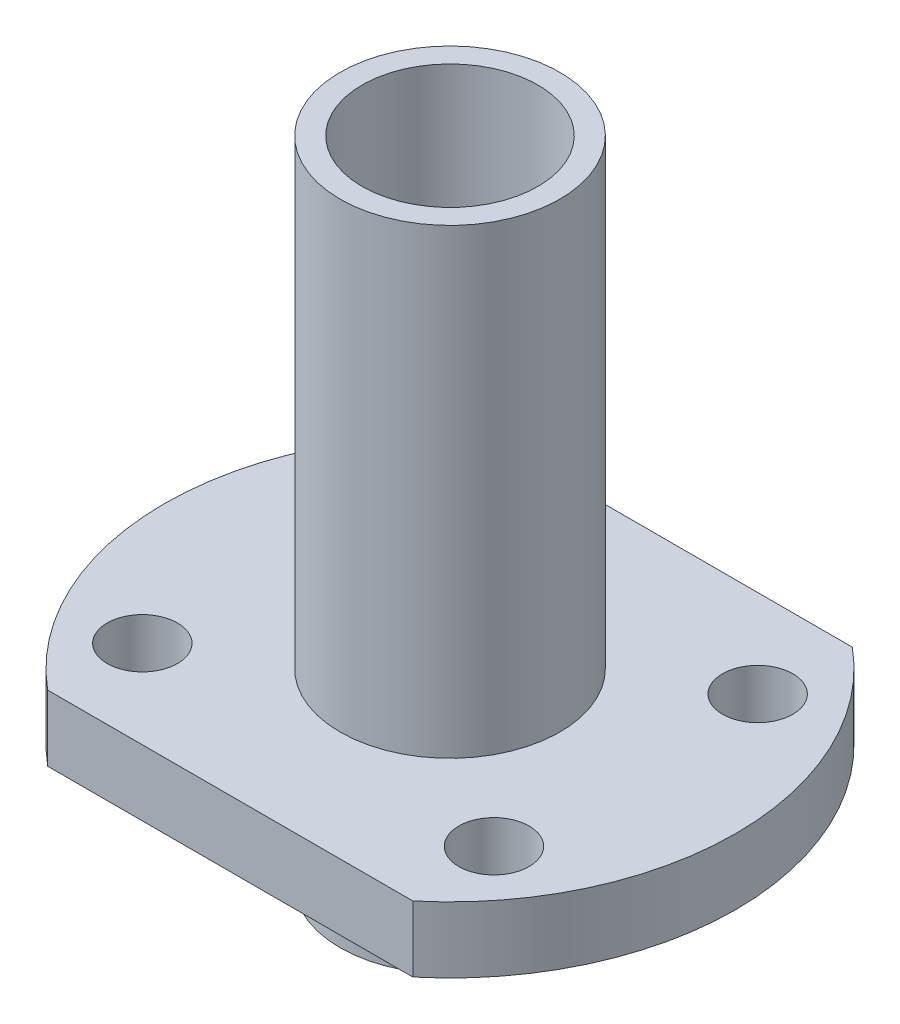
SolidWorks part; units mm, degrees
material "AISI 304"
ref_plane "Front Plane" through (0, 0, 0) normal (0, 0, 1) x (1, 0, 0)
ref_plane "Top Plane" through (0, 0, 0) normal (0, 1, 0) x (1, 0, 0)
ref_plane "Right Plane" through (0, 0, 0) normal (1, 0, 0) x (0, 0, -1)
sketch "Sketch1" plane through (0, 0, 0) normal (0, 1, 0) x (1, 0, 0)
  circle A0 centre (0, 0) radius 5
  dimension "D1" = 10
extrude "Boss-Extrude1" add sketch "Sketch1" along normal blind 29.5 contours A0
ref_plane "Plane1" through (0, 5.5, 0) normal (0, 1, 0) x (1, 0, 0)
sketch "Sketch2" plane through (0, 5.5, 0) normal (0, 1, 0) x (1, 0, 0)
  line L1 (-13, 10) -> (13, 10)
  line L2 (-13, 10) -> (-13, -10)
  line L3 (-13, -10) -> (13, -10)
  line L4 (13, 10) -> (13, -10)
  line L5 (-13, 10) -> (13, -10) construction
  line L6 (-13, -10) -> (13, 10) construction
  circle A0 centre (0, 0) radius 13
  dimension "D1" = 26
  dimension "D2" = 20
extrude "Boss-Extrude2" add sketch "Sketch2" along normal blind 3 contours L3 A0 L1
sketch "Sketch3" plane through (0, 29.5, 0) normal (0, 1, 0) x (1, 0, 0)
  circle A0 centre (0, 0) radius 4
  dimension "D1" = 8
extrude "Cut-Extrude1" cut sketch "Sketch3" against normal through all
sketch "Sketch4" plane through (0, 8.5, 0) normal (0, 1, 0) x (1, 0, 0)
  line L1 (8, -6) -> (-8, -6)
  line L2 (8, -6) -> (8, 6)
  line L3 (8, 6) -> (-8, 6)
  line L4 (-8, -6) -> (-8, 6)
  line L5 (8, -6) -> (-8, 6) construction
  line L6 (8, 6) -> (-8, -6) construction
  point P0 (0, 0)
  dimension "D1" = 12
  dimension "D2" = 16
hole_wizard "Ø3.2 (3.2) Diameter Hole1" positions "3DSketch1" profile "Sketch5" hole size "Ø3.2" standard "ISO" end condition through all
sketch3d "3DSketch1"
  point P0 (8, 8.5, 6)
  point P3 (8, 8.5, -6)
  point P6 (-8, 8.5, -6)
  point P9 (-8, 8.5, 6)
sketch "Sketch5" plane through (8, 8.5, 6) normal (1, 0, 0) x (0, 0, 1)
  line L0 (0, 0) -> (0, 8.5)
  line L1 (0, 8.5) -> (1.6, 8.5)
  line L2 (1.6, 8.5) -> (1.6, 0)
  line L5 (1.6, 0) -> (0, 0)
  line L11 (0, -6.35) -> (0, 107.95) construction
  dimension "Thru Hole Dia." = 3.2
  dimension "Thru Hole Depth" = 8.5
